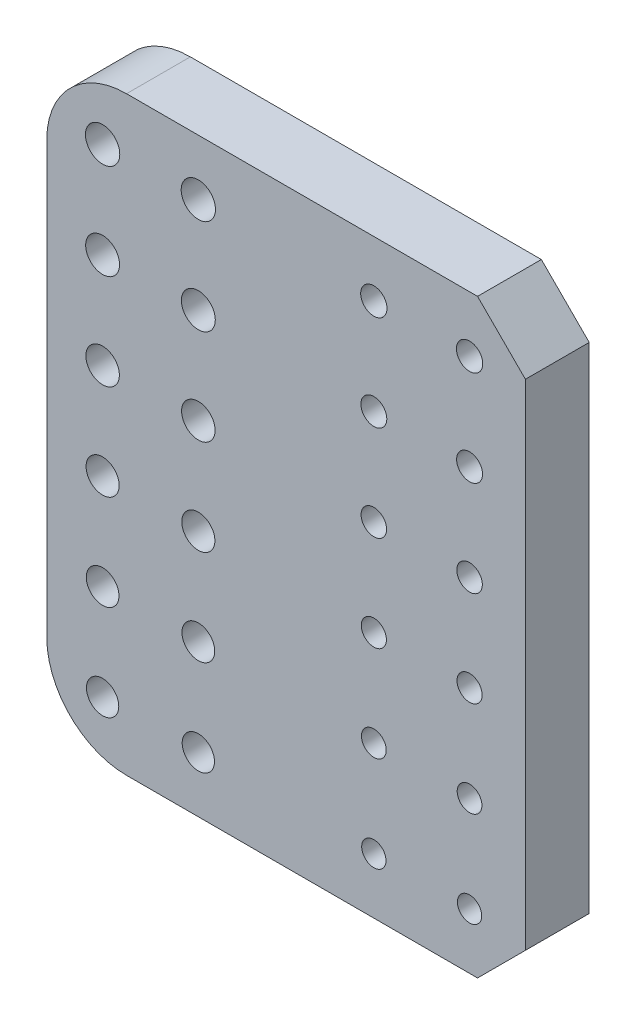
SolidWorks part; units mm, degrees
ref_plane "Front Plane" through (0, 0, 0) normal (0, 0, 1) x (1, 0, 0)
ref_plane "Top Plane" through (0, 0, 0) normal (0, 1, 0) x (1, 0, 0)
ref_plane "Right Plane" through (0, 0, 0) normal (1, 0, 0) x (0, 0, -1)
sketch "Sketch1" plane through (0, 0, 0) normal (0, 0, 1) x (1, 0, 0)
  line L1 (30, 37) -> (-30, 37)
  line L2 (30, 37) -> (30, -37)
  line L3 (30, -37) -> (-30, -37)
  line L4 (-30, 37) -> (-30, -37)
  line L5 (30, 37) -> (-30, -37) construction
  line L6 (30, -37) -> (-30, 37) construction
  point P0 (0, 0)
  dimension "D1" = 60
  dimension "D2" = 74
extrude "Boss-Extrude1" add sketch "Sketch1" along normal blind 12
sketch "Sketch3" plane through (0, 0, 12) normal (0, 0, 1) x (1, 0, 0)
  line L0 (-30, -37) -> (-23, -37) construction
  line L1 (-30, -37) -> (30, -37) construction
  line L2 (-23, -37) -> (-23, -30) construction
  line L3 (30, -37) -> (23, -37) construction
  line L4 (23, -37) -> (23, -30) construction
  circle A0 centre (-23, -30) radius 1.65
  circle A1 centre (23, -30) radius 1.15
  circle A2 centre (-11, -30) radius 1.65
  circle A3 centre (-11, -18) radius 1.65
  circle A4 centre (-11, -6) radius 1.65
  circle A5 centre (-11, 6) radius 1.65
  circle A6 centre (-23, -18) radius 1.65
  circle A7 centre (-23, -6) radius 1.65
  circle A8 centre (-23, 6) radius 1.65
  circle A9 centre (11, -30) radius 1.15
  circle A10 centre (11, -18) radius 1.15
  circle A11 centre (11, -6) radius 1.15
  circle A12 centre (11, 6) radius 1.15
  circle A13 centre (23, -18) radius 1.15
  circle A14 centre (23, -6) radius 1.15
  circle A15 centre (23, 6) radius 1.15
  circle A16 centre (-23, 18) radius 1.65
  circle A17 centre (-11, 18) radius 1.65
  circle A18 centre (-23, 30) radius 1.65
  circle A19 centre (-11, 30) radius 1.65
  circle A20 centre (23, 18) radius 1.15
  circle A21 centre (11, 18) radius 1.15
  circle A22 centre (23, 30) radius 1.15
  circle A23 centre (11, 30) radius 1.15
  dimension "D2" = 3.3
  dimension "D3" = 2.3
  dimension "D1" = 7
  dimension "D6" = 12
  dimension "D7" = 12
  dimension "D4" = 2
  dimension "D5" = 6
  dimension "D8" = 2
  dimension "D9" = 6
extrude "Cut-Extrude1" cut sketch "Sketch3" against normal through all
sketch "Sketch4" plane through (0, 0, 12) normal (0, 0, 1) x (1, 0, 0)
  circle A1 centre (-23, -30) radius 2.9
  circle A3 centre (-11, -30) radius 2.9
  circle A4 centre (-11, -18) radius 2.9
  circle A5 centre (-11, -6) radius 2.9
  circle A6 centre (-11, 6) radius 2.9
  circle A7 centre (-23, -18) radius 2.9
  circle A8 centre (-23, -6) radius 2.9
  circle A9 centre (-23, 6) radius 2.9
  circle A10 centre (11, -30) radius 2.4
  circle A11 centre (23, -30) radius 2.4
  circle A12 centre (23, -18) radius 2.4
  circle A13 centre (23, -6) radius 2.4
  circle A14 centre (23, 6) radius 2.4
  circle A15 centre (11, -18) radius 2.4
  circle A16 centre (11, -6) radius 2.4
  circle A17 centre (11, 6) radius 2.4
  circle A18 centre (-23, 18) radius 2.9
  circle A19 centre (-11, 18) radius 2.9
  circle A20 centre (-23, 30) radius 2.9
  circle A21 centre (-11, 30) radius 2.9
  circle A22 centre (11, 18) radius 2.4
  circle A23 centre (23, 18) radius 2.4
  circle A24 centre (11, 30) radius 2.4
  circle A25 centre (23, 30) radius 2.4
  dimension "D1" = 5.8
  dimension "D4" = 4.8
  dimension "D2" = 2
  dimension "D3" = 6
  dimension "D5" = 2
  dimension "D6" = 6
chamfer "Chamfer1" distance 6 angle 45 2 edges at (30, 37, 6) (30, -37, 6)
fillet "Fillet1" radius 10 2 edges at (-30, -37, 6) (-30, 37, 6)
extrude "Cut-Extrude2" cut sketch "Sketch4" against normal blind 4
sketch "Sketch6" plane through (0, 0, 8) normal (0, 0, 1) x (1, 0, 0)
  circle A0 centre (-23, 30) radius 2.15
  circle A1 centre (-23, 18) radius 2.125
  circle A2 centre (-23, 6) radius 2.1
  circle A3 centre (-23, -6) radius 2.075
  circle A4 centre (-23, -18) radius 2.05
  circle A5 centre (-23, -30) radius 2.025
  circle A6 centre (-11, 30) radius 2.15
  circle A7 centre (11, -30) radius 1.525
  circle A8 centre (11, -18) radius 1.55
  circle A9 centre (11, -6) radius 1.575
  circle A10 centre (11, 6) radius 1.6
  circle A11 centre (11, 18) radius 1.625
  circle A12 centre (11, 30) radius 1.65
  circle A13 centre (-11, 18) radius 2.125
  circle A14 centre (-11, 6) radius 2.1
  circle A15 centre (-11, -6) radius 2.075
  circle A16 centre (-11, -18) radius 2.05
  circle A17 centre (-11, -30) radius 2.025
  circle A18 centre (23, -30) radius 1.525
  circle A19 centre (23, -18) radius 1.55
  circle A20 centre (23, -6) radius 1.575
  circle A21 centre (23, 6) radius 1.6
  circle A22 centre (23, 18) radius 1.625
  circle A23 centre (23, 30) radius 1.65
  dimension "D1" = 4.05
  dimension "D2" = 4.1
  dimension "D3" = 4.15
  dimension "D4" = 4.2
  dimension "D5" = 4.25
  dimension "D6" = 4.3
  dimension "D7" = 3.3
  dimension "D8" = 3.25
  dimension "D9" = 3.2
  dimension "D10" = 3.15
  dimension "D11" = 3.1
  dimension "D12" = 3.05
  dimension "D13" = 2
  dimension "D14" = 2
extrude "Cut-Extrude3" cut sketch "Sketch6" against normal blind 3.1
sketch "Sketch8" plane through (-30, 0, 0) normal (-1, 0, 0) x (0, 0, 1)
  line L0 (12, -37) -> (0, -37) construction
  line L1 (12, 37) -> (8, 37)
  line L2 (12, 37) -> (12, -37)
  line L3 (12, -37) -> (8, -37)
  line L4 (8, 37) -> (8, -37)
  line L5 (12, 37) -> (8, -37) construction
  line L6 (12, -37) -> (8, 37) construction
  point P4 (10, 0)
  dimension "D1" = 4
extrude "Cut-Extrude4" cut sketch "Sketch8" against normal through all
